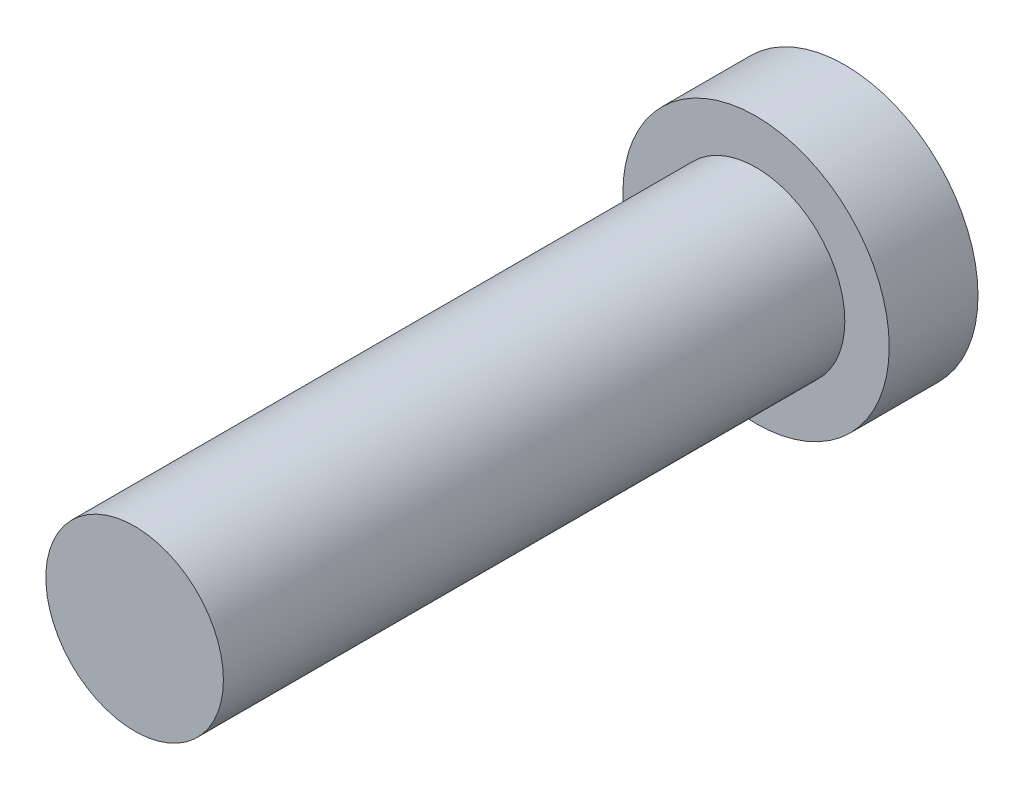
SolidWorks part; units mm, degrees
ref_plane "Front Plane" through (0, 0, 0) normal (0, 0, 1) x (1, 0, 0)
ref_plane "Top Plane" through (0, 0, 0) normal (0, 1, 0) x (1, 0, 0)
ref_plane "Right Plane" through (0, 0, 0) normal (1, 0, 0) x (0, 0, -1)
sketch "Sketch1" plane through (0, 0, 0) normal (0, 0, 1) x (1, 0, 0)
  circle A0 centre (0, 0) radius 5
  dimension "D1" = 10
extrude "Boss-Extrude1" add sketch "Sketch1" along normal blind 35
sketch "Sketch2" plane through (0, 0, 0) normal (0, 0, -1) x (-1, 0, 0)
  circle A0 centre (0, 0) radius 7.5
  dimension "D1" = 15
extrude "Boss-Extrude2" add sketch "Sketch2" along normal blind 5
